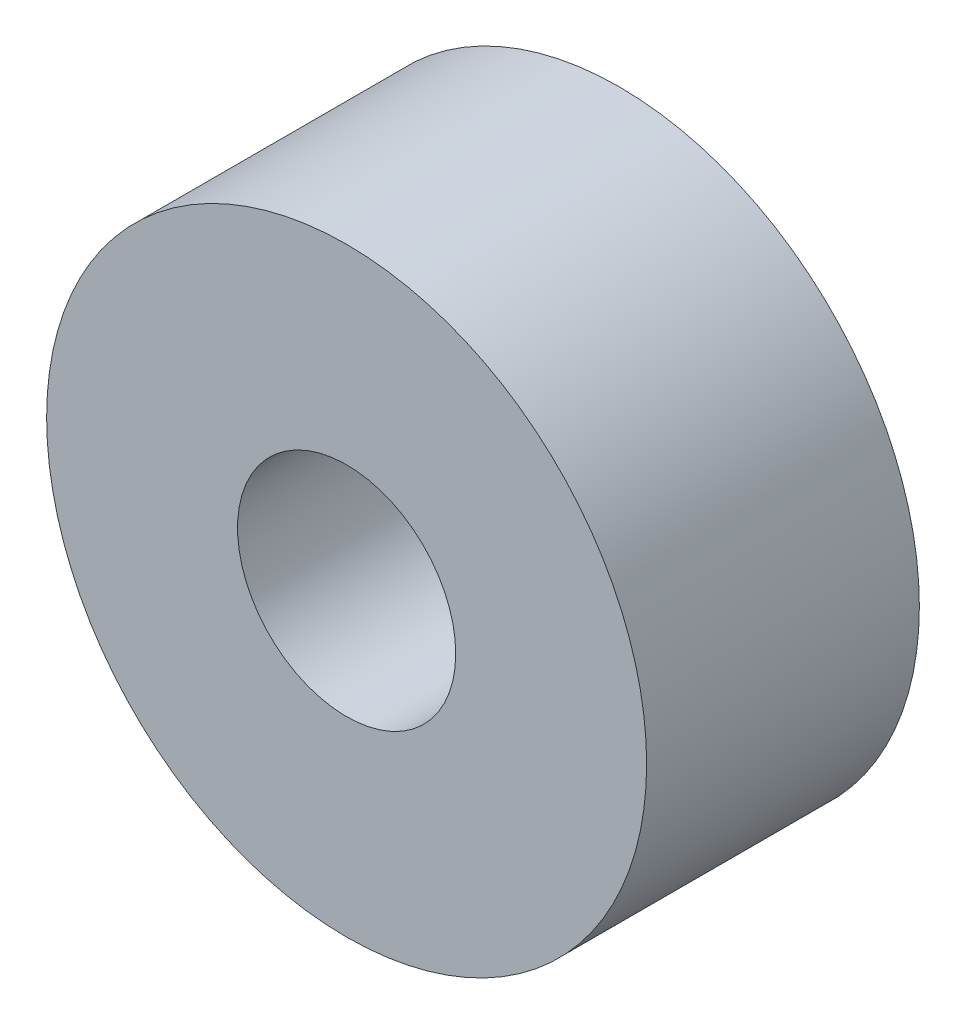
SolidWorks part; units mm, degrees
ref_plane "Front Plane" through (0, 0, 0) normal (0, 0, 1) x (1, 0, 0)
ref_plane "Top Plane" through (0, 0, 0) normal (0, 1, 0) x (1, 0, 0)
ref_plane "Right Plane" through (0, 0, 0) normal (1, 0, 0) x (0, 0, -1)
sketch "Sketch1" plane through (0, 0, 0) normal (0, 0, 1) x (1, 0, 0)
  circle A0 centre (0, 0) radius 3.175
  circle A1 centre (0, 0) radius 8.7312
  dimension "D1" = 6.35
  dimension "D2" = 17.4625
extrude "Boss-Extrude1" add sketch "Sketch1" along normal blind 7.9375
